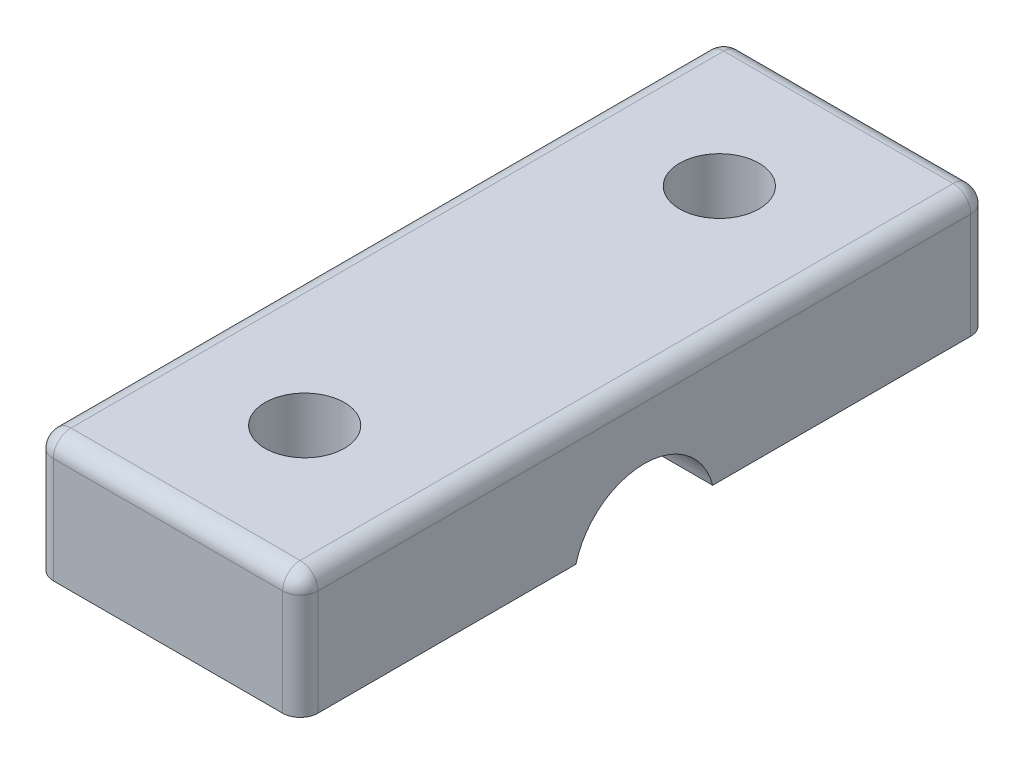
SolidWorks part; units mm, degrees
ref_plane "Front Plane" through (0, 0, 0) normal (0, 0, 1) x (1, 0, 0)
ref_plane "Top Plane" through (0, 0, 0) normal (0, 1, 0) x (1, 0, 0)
ref_plane "Right Plane" through (0, 0, 0) normal (1, 0, 0) x (0, 0, -1)
sketch "Sketch1" plane through (0, 0, 0) normal (0, 1, 0) x (1, 0, 0)
  line L0 (0, 19.5) -> (15, 19.5) construction
  line L1 (0, 39) -> (15, 39)
  line L2 (0, 39) -> (0, 0)
  line L3 (0, 0) -> (15, 0)
  line L4 (15, 39) -> (15, 0)
  circle A0 centre (7.5, 31.25) radius 2.25
  circle A1 centre (7.5, 7.75) radius 2.25
  point P8 (7.5, 39)
  dimension "D3" = 4.5
  dimension "D1" = 15
  dimension "D2" = 39
  dimension "D4" = 7.75
extrude "Boss-Extrude1" add sketch "Sketch1" along normal blind 8
fillet "Fillet2" radius 1 8 edges at (7.5, 8, -39) (0, 8, -19.5) (15, 8, -19.5) (7.5, 8, 0) (0, 4, 0) (15, 4, 0) (15, 4, -39) (0, 4, -39)
sketch "Sketch2" plane through (0, 0, 0) normal (-1, 0, 0) x (0, 0, 1)
  line L0 (-23.373, 1) -> (-45.3024, 1)
  line L1 (-38, 8) -> (-1, 8) construction
  line L2 (-38, 0) -> (-1, 0) construction
  line L3 (4.6976, 1) -> (-15.627, 1)
  line L4 (4.6976, 1) -> (4.6976, -1)
  line L5 (4.6976, -1) -> (-45.3024, -1)
  line L6 (-45.3024, 1) -> (-45.3024, -1)
  arc A0 (-23.373, 1) -> (-15.627, 1) centre (-19.5, 0) cw
  point P9 (-19.5, 4)
  point P15 (-19.5, 0)
  dimension "D1" = 4
  dimension "D2" = 4
  dimension "D3" = 3
  dimension "D4" = 2
  dimension "D5" = 50
extrude "Cut-Extrude1" cut sketch "Sketch2" against normal up to surface (15 mm away) up to face at (15, 3.5, -19.5)
